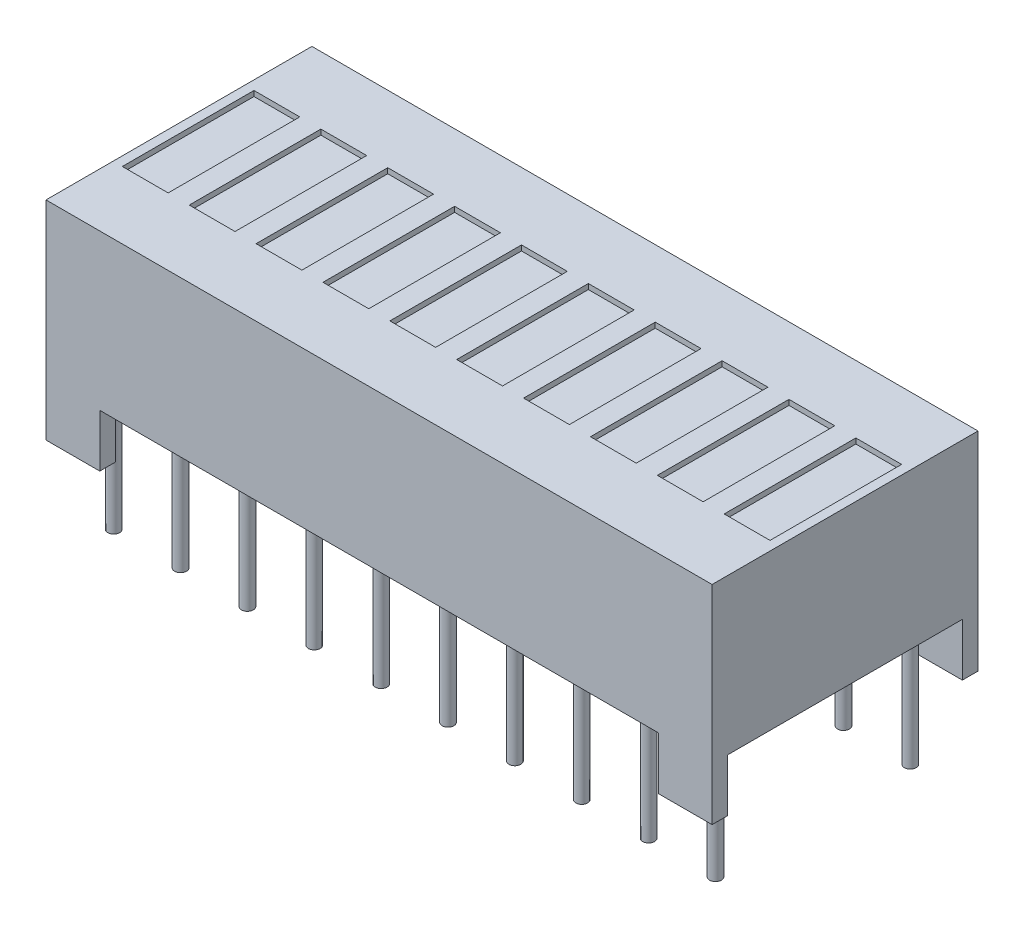
SolidWorks part; units mm, degrees
ref_plane "前视基准面" through (0, 0, 0) normal (0, 0, 1) x (1, 0, 0)
ref_plane "上视基准面" through (0, 0, 0) normal (0, 1, 0) x (1, 0, 0)
ref_plane "右视基准面" through (0, 0, 0) normal (1, 0, 0) x (0, 0, -1)
sketch "草图1" plane through (0, 0, 0) normal (0, 1, 0) x (1, 0, 0)
  line L0 (-34.1381, 0) -> (21.7243, 0) construction
  line L1 (-12.65, 5.05) -> (12.65, 5.05)
  line L2 (-12.65, 5.05) -> (-12.65, -5.05)
  line L3 (-12.65, -5.05) -> (12.65, -5.05)
  line L4 (12.65, 5.05) -> (12.65, -5.05)
  line L5 (0, 13.1223) -> (0, -10.626) construction
  dimension "D1" = 25.3
  dimension "D2" = 10.1
extrude "凸台-拉伸1" add sketch "草图1" along normal blind 7.9
sketch "草图3" plane through (0, 7.9, 0) normal (0, 1, 0) x (1, 0, 0)
  line L0 (0, 6.8495) -> (0, -9.5142) construction
  line L1 (-17.0392, 0) -> (15.2002, 0) construction
  line L2 (-1.27, 3.956) -> (-1.27, -4.9713) construction
  line L3 (-2.14, 2.5) -> (-0.4, 2.5)
  line L4 (-2.14, 2.5) -> (-2.14, -2.5)
  line L5 (-2.14, -2.5) -> (-0.4, -2.5)
  line L6 (-0.4, 2.5) -> (-0.4, -2.5)
  line L7 (0.4, 2.5) -> (2.14, 2.5)
  line L8 (0.4, 2.5) -> (0.4, -2.5)
  line L9 (0.4, -2.5) -> (2.14, -2.5)
  line L10 (2.14, 2.5) -> (2.14, -2.5)
  line L11 (2.94, 2.5) -> (4.68, 2.5)
  line L12 (2.94, 2.5) -> (2.94, -2.5)
  line L13 (2.94, -2.5) -> (4.68, -2.5)
  line L14 (4.68, 2.5) -> (4.68, -2.5)
  line L15 (5.48, 2.5) -> (7.22, 2.5)
  line L16 (5.48, 2.5) -> (5.48, -2.5)
  line L17 (5.48, -2.5) -> (7.22, -2.5)
  line L18 (7.22, 2.5) -> (7.22, -2.5)
  line L19 (8.02, 2.5) -> (9.76, 2.5)
  line L20 (8.02, 2.5) -> (8.02, -2.5)
  line L21 (8.02, -2.5) -> (9.76, -2.5)
  line L22 (9.76, 2.5) -> (9.76, -2.5)
  line L23 (10.56, 2.5) -> (12.3, 2.5)
  line L24 (10.56, 2.5) -> (10.56, -2.5)
  line L25 (10.56, -2.5) -> (12.3, -2.5)
  line L26 (12.3, 2.5) -> (12.3, -2.5)
  line L27 (-4.68, 2.5) -> (-2.94, 2.5)
  line L28 (-4.68, 2.5) -> (-4.68, -2.5)
  line L29 (-4.68, -2.5) -> (-2.94, -2.5)
  line L30 (-2.94, 2.5) -> (-2.94, -2.5)
  line L31 (-7.22, 2.5) -> (-5.48, 2.5)
  line L32 (-7.22, 2.5) -> (-7.22, -2.5)
  line L33 (-7.22, -2.5) -> (-5.48, -2.5)
  line L34 (-5.48, 2.5) -> (-5.48, -2.5)
  line L35 (-9.76, 2.5) -> (-8.02, 2.5)
  line L36 (-9.76, 2.5) -> (-9.76, -2.5)
  line L37 (-9.76, -2.5) -> (-8.02, -2.5)
  line L38 (-8.02, 2.5) -> (-8.02, -2.5)
  line L39 (-12.3, 2.5) -> (-10.56, 2.5)
  line L40 (-12.3, 2.5) -> (-12.3, -2.5)
  line L41 (-12.3, -2.5) -> (-10.56, -2.5)
  line L42 (-10.56, 2.5) -> (-10.56, -2.5)
  dimension "D1" = 5
  dimension "D2" = 1.74
  dimension "D3" = 1.27
  dimension "D4" = 6
  dimension "D5" = 5
extrude "切除-拉伸2" cut sketch "草图3" against normal blind 0.2
sketch "草图2" plane through (0, 0, 0) normal (0, -1, 0) x (1, 0, 0)
  line L0 (0, 7.7799) -> (0, -7.6235) construction
  line L1 (-12.65, 5.05) -> (-10.6078, 5.05)
  line L2 (-12.65, 5.05) -> (-12.65, 4.4563)
  line L3 (-12.65, 4.4563) -> (-10.6078, 4.4563)
  line L4 (-10.6078, 5.05) -> (-10.6078, 4.4563)
  line L5 (-15.1428, 0) -> (15.2732, 0) construction
  line L6 (10.6078, 5.05) -> (10.6078, 4.4563)
  line L7 (12.65, 4.4563) -> (10.6078, 4.4563)
  line L8 (12.65, 5.05) -> (12.65, 4.4563)
  line L9 (12.65, 5.05) -> (10.6078, 5.05)
  line L10 (12.65, -5.05) -> (10.6078, -5.05)
  line L11 (12.65, -5.05) -> (12.65, -4.4563)
  line L12 (12.65, -4.4563) -> (10.6078, -4.4563)
  line L13 (10.6078, -5.05) -> (10.6078, -4.4563)
  line L14 (-10.6078, -5.05) -> (-10.6078, -4.4563)
  line L15 (-12.65, -4.4563) -> (-10.6078, -4.4563)
  line L16 (-12.65, -5.05) -> (-12.65, -4.4563)
  line L17 (-12.65, -5.05) -> (-10.6078, -5.05)
extrude "切除-拉伸1" cut sketch "草图2" against normal blind 2 flip side to cut
sketch "草图4" plane through (0, 2, 0) normal (0, -1, 0) x (1, 0, 0)
  line L0 (-16.3939, 0) -> (15.0386, 0) construction
  line L1 (0, 6.7895) -> (0, -7.2065) construction
  circle A0 centre (-1.27, 3.7) radius 0.225
  circle A1 centre (-1.27, -3.7) radius 0.225
  circle A2 centre (1.27, 3.7) radius 0.225
  circle A3 centre (1.27, -3.7) radius 0.225
  circle A4 centre (3.81, 3.7) radius 0.225
  circle A5 centre (3.81, -3.7) radius 0.225
  circle A6 centre (6.35, 3.7) radius 0.225
  circle A7 centre (6.35, -3.7) radius 0.225
  circle A8 centre (8.89, 3.7) radius 0.225
  circle A9 centre (8.89, -3.7) radius 0.225
  circle A10 centre (11.43, 3.7) radius 0.225
  circle A11 centre (11.43, -3.7) radius 0.225
  circle A12 centre (-3.81, 3.7) radius 0.225
  circle A13 centre (-3.81, -3.7) radius 0.225
  circle A14 centre (-6.35, 3.7) radius 0.225
  circle A15 centre (-6.35, -3.7) radius 0.225
  circle A16 centre (-8.89, 3.7) radius 0.225
  circle A17 centre (-8.89, -3.7) radius 0.225
  circle A18 centre (-11.43, 3.7) radius 0.225
  circle A19 centre (-11.43, -3.7) radius 0.225
  dimension "D1" = 0.45
  dimension "D2" = 1.27
  dimension "D3" = 7.4
  dimension "D4" = 6
  dimension "D5" = 5
extrude "凸台-拉伸2" add sketch "草图4" along normal blind 5
